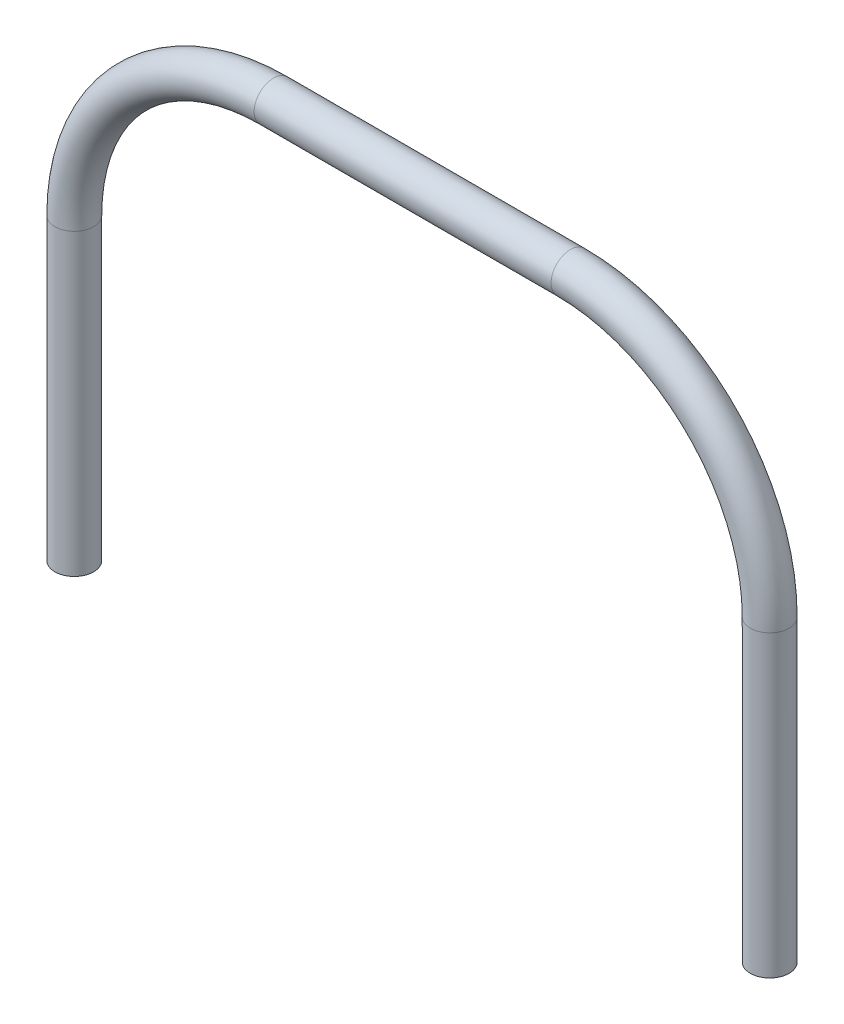
SolidWorks part; units mm, degrees
ref_plane "Alzado" through (0, 0, 0) normal (0, 0, 1) x (1, 0, 0)
ref_plane "Planta" through (0, 0, 0) normal (0, 1, 0) x (1, 0, 0)
ref_plane "Vista lateral" through (0, 0, 0) normal (1, 0, 0) x (0, 0, -1)
sketch "Croquis1" plane through (0, 0, 0) normal (0, 0, 1) x (1, 0, 0)
  line L0 (0, 0) -> (0, 150)
  line L1 (100, 250) -> (249, 250)
  line L2 (349, 150) -> (349, 0)
  arc A0 (249, 250) -> (349, 150) centre (249, 150) cw
  arc A1 (0, 150) -> (100, 250) centre (100, 150) cw
  point P7 (349, 250)
  point P10 (0, 250)
  dimension "D3" = 100
  dimension "D1" = 250
  dimension "D2" = 349
sketch "Croquis2" plane through (0, 0, 0) normal (0, 1, 0) x (1, 0, 0)
  circle A0 centre (0, 0) radius 9.75
  dimension "D1" = 19.5
sweep "Barrer1" add profiles "Croquis2" path "Croquis1"
